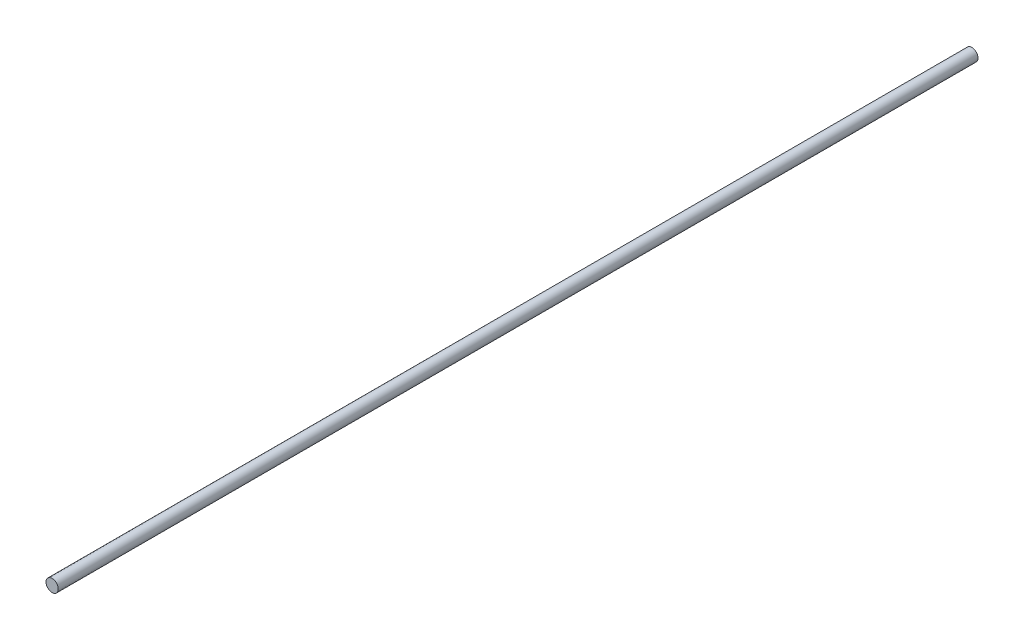
SolidWorks part; units mm, degrees
ref_plane "Front Plane" through (0, 0, 0) normal (0, 0, 1) x (1, 0, 0)
ref_plane "Top Plane" through (0, 0, 0) normal (0, 1, 0) x (1, 0, 0)
ref_plane "Right Plane" through (0, 0, 0) normal (1, 0, 0) x (0, 0, -1)
sketch "Sketch2" plane through (0, 0, 0) normal (0, 0, 1) x (1, 0, 0)
  circle A0 centre (0, 0) radius 2
  dimension "D1" = 4
extrude "Boss-Extrude1" add sketch "Sketch2" along normal blind 300
